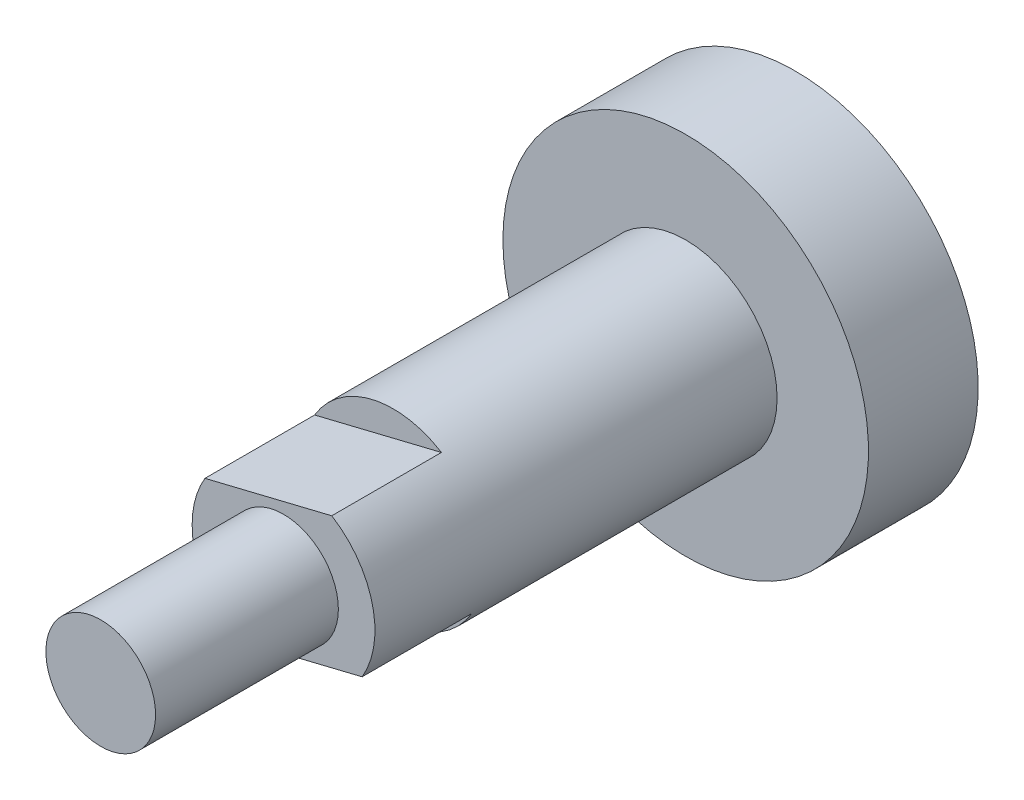
SolidWorks part; units mm, degrees
ref_plane "Front Plane" through (0, 0, 0) normal (0, 0, 1) x (1, 0, 0)
ref_plane "Top Plane" through (0, 0, 0) normal (0, 1, 0) x (1, 0, 0)
ref_plane "Right Plane" through (0, 0, 0) normal (1, 0, 0) x (0, 0, -1)
sketch "Sketch1" plane through (0, 0, 0) normal (0, 0, 1) x (1, 0, 0)
  circle A0 centre (0, 0) radius 5
  dimension "D1" = 10
extrude "Boss-Extrude1" add sketch "Sketch1" along normal blind 22
sketch "Sketch2" plane through (0, 0, 22) normal (0, 0, 1) x (1, 0, 0)
  line L0 (2.6383, 4.2473) -> (-4.2992, 2.5528)
  line L1 (-2.6383, -4.2473) -> (4.2992, -2.5528)
  arc A0 (-2.6383, -4.2473) -> (4.2992, -2.5528) centre (0, 0) ccw
  arc A1 (2.6383, 4.2473) -> (-4.2992, 2.5528) centre (0, 0) ccw
  dimension "D2" = 10
  dimension "D3" = 3.5
  dimension "D1" = 3.5
  dimension "D4" = 360
extrude "Cut-Extrude1" cut sketch "Sketch2" against normal blind 6
sketch "Sketch3" plane through (0, 0, 22) normal (0, 0, 1) x (1, 0, 0)
  circle A0 centre (0, 0) radius 3
extrude "Boss-Extrude2" add sketch "Sketch3" along normal blind 10
sketch "Sketch4" plane through (0, 0, 0) normal (0, 0, -1) x (-1, 0, 0)
  circle A0 centre (0, 0) radius 10
  dimension "D1" = 20
extrude "Boss-Extrude3" add sketch "Sketch4" along normal blind 6
sketch "Sketch5" plane through (0, 0, -6) normal (0, 0, -1) x (-1, 0, 0)
  circle A0 centre (0, 0) radius 20
extrude "Boss-Extrude4" [suppressed] add sketch "Sketch5" along normal blind 3 contours A0
sketch "Sketch6" [suppressed] plane through (0, 0, -9) normal (0, 0, -1) x (-1, 0, 0)
  circle A0 centre (-16, 0) radius 2
  circle A1 centre (0, 0) radius 20 construction
  circle A2 centre (0, 16) radius 2
  circle A3 centre (16, 0) radius 2
  circle A4 centre (0, -16) radius 2
  point P13 (0, 0)
  dimension "D1" = 4
  dimension "D2" = 16
  dimension "D3" = 4
extrude "Cut-Extrude2" [suppressed] cut sketch "Sketch6" against normal blind 3
